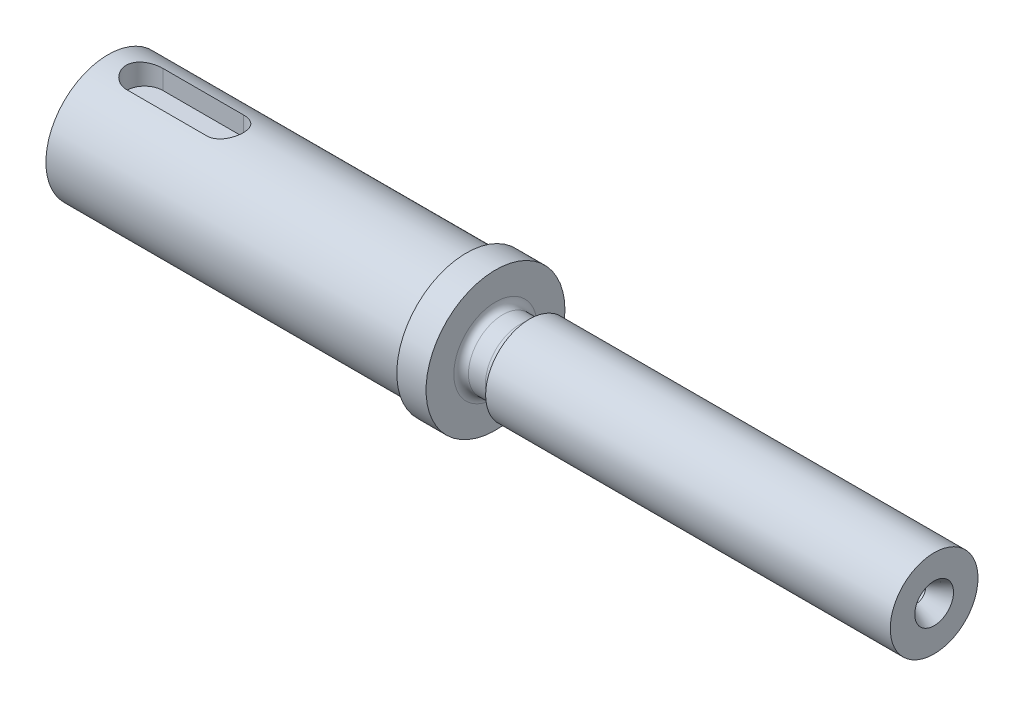
SolidWorks part; units mm, degrees
material "1.0533 (ZSt50-2 / E295)"
ref_plane "Vorne" through (0, 0, 0) normal (0, 0, 1) x (1, 0, 0)
ref_plane "Oben" through (0, 0, 0) normal (0, 1, 0) x (1, 0, 0)
ref_plane "Rechts" through (0, 0, 0) normal (1, 0, 0) x (0, 0, -1)
sketch "Skizze1" plane through (0, 0, 0) normal (0, 0, 1) x (1, 0, 0)
  line L0 (13.5135, 0) -> (-139.8639, 0) construction
  line L3 (-113, 0) -> (-113, 8.5)
  line L4 (-113, 8.5) -> (-64, 8.5)
  line L5 (-64, 8.5) -> (-64, 9.5)
  line L6 (-64, 9.5) -> (-60, 9.5)
  line L7 (-60, 9.5) -> (-60, 6)
  line L9 (0, 6) -> (0, 0)
  line L10 (0, 0) -> (-113, 0)
  line L11 (-60, 6) -> (0, 6)
  dimension "D1" = 60
  dimension "D3" = 17
  dimension "D4" = 49
  dimension "D5" = 12
  dimension "D7" = 19
  dimension "D9" = 4
revolve "Rotation1" add sketch "Skizze1" angle 360 about L0
cosmetic thread "Gewindedarstellung3" parameters "D1"=57.5, "D2"=10.5
ref_plane "Ebene1" through (0, 8.5, 0) normal (0, 1, 0) x (-1, 0, 0)
sketch "Skizze2" plane through (0, 8.5, 0) normal (0, 1, 0) x (-1, 0, 0)
  line L0 (83.2372, 0) -> (121.3052, 0) construction
  line L2 (108, 2.5) -> (97, 2.5)
  line L3 (113, -8.5) -> (113, 8.5) construction
  line L4 (108, -2.5) -> (97, -2.5)
  arc A0 (97, 2.5) -> (97, -2.5) centre (97, 0) ccw
  arc A1 (108, 2.5) -> (108, -2.5) centre (108, 0) cw
  dimension "D3" = 2.5
  dimension "D2" = 11
  dimension "D1" = 5
  dimension "D4" = 5
extrude "Schnitt-Linear austragen1" cut sketch "Skizze2" against normal blind 3
hole_wizard "M6 Gewindebohrung1" positions "Skizze4" profile "Skizze3" tap size "M6" standard "ISO"
sketch "Skizze4" plane through (-113, 0, 0) normal (-1, 0, 0) x (0, 0, 1)
  point P0 (0, 0)
sketch "Skizze3" plane through (-113, 0, 0) normal (0, 1, 0) x (0, 0, 1)
  line L0 (0, 0) -> (0, 21.5022)
  line L1 (0, 21.5022) -> (2.5, 20)
  line L2 (2.5, 20) -> (2.5, 0.5)
  line L3 (2.5, 0.5) -> (3, 0)
  line L5 (3, 0) -> (0, 0)
  line L6 (-2.5, 0.5) -> (-3, 0) construction
  line L10 (0, 21.5022) -> (-2.5, 20) construction
  line L11 (0, -6.35) -> (0, 107.95) construction
  dimension "Bohrerdurchmesser" = 5
  dimension "Bohrungstiefe" = 20
  dimension "Senkdurchmesser (Oben)" = 6
  dimension "Senkwinkel (Oben)" = 90
  dimension "Spitzenwinkel" = 118
cosmetic thread "Bohrungsgewinde1" parameters "D1"=15, "D2"=6
sketch "Skizze21" plane through (-60, 7.6867, -0.5058) normal (1, 0, 0) x (0, 0, -1)
  line L0 (-0.5058, -1.6867) -> (-0.5058, -7.6867) construction
  line L1 (-0.5058, -7.6867) -> (5.4942, -7.6867) construction
  circle A0 centre (-0.5058, -7.6867) radius 6
  circle A1 centre (-0.5058, -7.6867) radius 6 construction
ref_plane "Ebene11" through (-60, 0, 0) normal (0, 0, -1) x (-1, 0, 0)
sketch "Skizze31" plane through (-60, 0, 0) normal (0, 0, -1) x (-1, 0, 0)
  line L0 (-4.6506, 6) -> (-4.1887, 5.2)
  line L1 (-3.3226, 4.7) -> (-1, 4.7)
  line L2 (0, 5.7) -> (0, 6)
  line L3 (0, 6) -> (-4.6506, 6)
  line L4 (0, 6) -> (0, 0) construction
  line L6 (13.6772, 0) -> (-13.6772, 0) construction
  arc A0 (-1, 4.7) -> (0, 5.7) centre (-1, 5.7) ccw
  arc A1 (-4.1887, 5.2) -> (-3.3226, 4.7) centre (-3.3226, 5.7) ccw
  point P13 (-3.9, 4.7)
  dimension "r" = 1
  dimension "dg" = 9.4
  dimension "g1" = 3.9
  dimension "Auslaufwinkel" = 60
revolve "Schnitt-Rotation1" cut sketch "Skizze31" angle 360 about L6
other "DIN 76-1-A<1>"
sketch "Position" plane through (0, -2.1255, -0.3908) normal (1, 0, 0) x (0, 0, -1)
  line L0 (-2.3515, 2.1255) -> (-0.3908, 2.1255) construction
  line L1 (-0.3908, 2.1255) -> (-0.3908, 0.1647) construction
  circle A0 centre (-0.3908, 2.1255) radius 1.9607
  circle A1 centre (-0.3908, 2.1255) radius 6 construction
ref_plane "Ebene12" through (0, 0, 0) normal (0, -1, 0) x (1, 0, 0)
sketch "Skizze32" plane through (0, 0, 0) normal (0, -1, 0) x (0, 0, -1)
  line L0 (0, 0) -> (0, -4.7988) construction
  line L2 (0, -5.3511) -> (1.25, -4.6)
  line L3 (1.25, -4.6) -> (1.25, -2.4249)
  line L4 (1.25, -2.4249) -> (2.65, 0)
  line L5 (2.65, 0) -> (0, 0)
  line L6 (0, 0) -> (0, -5.3511)
  dimension "w1" = 30
  dimension "w2" = 59
  dimension "d1" = 2.5
  dimension "d2" = 5.3
  dimension "t1" = 4.6
revolve "Schnitt-Rotation11" cut sketch "Skizze32" angle 360 about L0
other "DIN 332 - A<1>"
